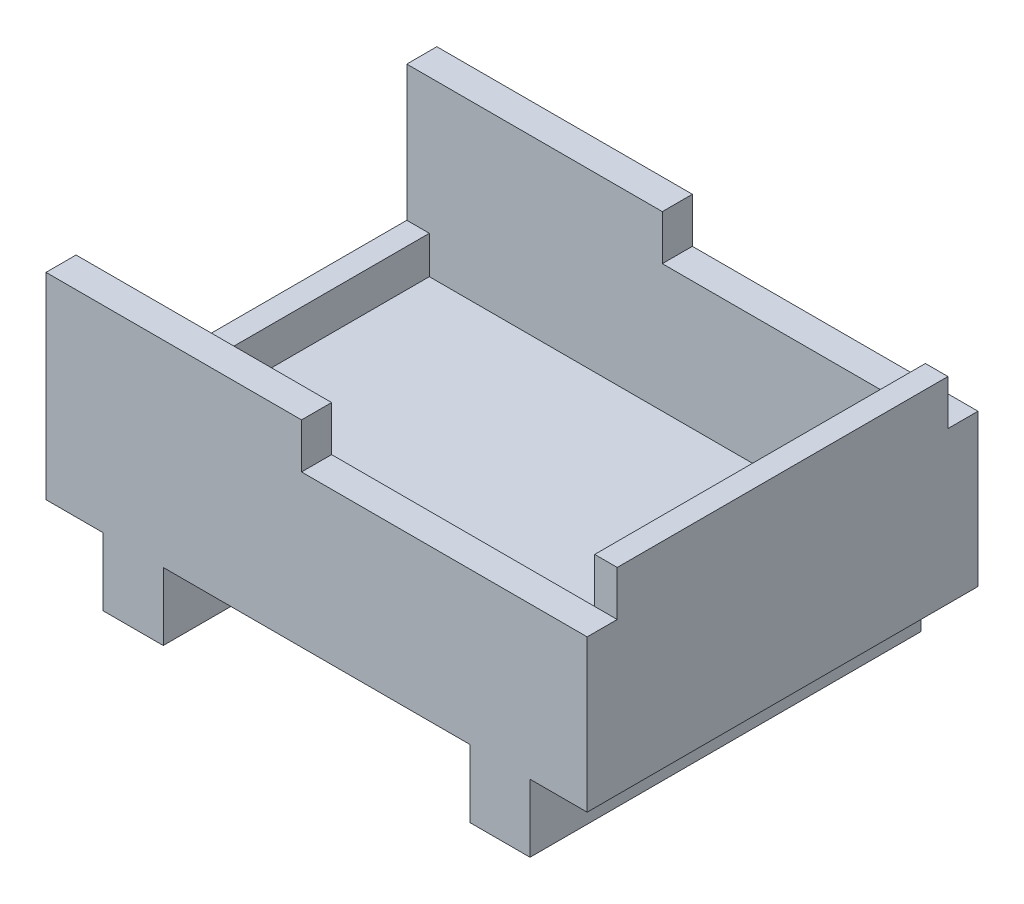
SolidWorks part; units mm, degrees
ref_plane "前视基准面" through (0, 0, 0) normal (0, 0, 1) x (1, 0, 0)
ref_plane "上视基准面" through (0, 0, 0) normal (0, 1, 0) x (1, 0, 0)
ref_plane "右视基准面" through (0, 0, 0) normal (1, 0, 0) x (0, 0, -1)
sketch "草图1" plane through (0, 0, 0) normal (0, 1, 0) x (1, 0, 0)
  line L1 (-18, 13) -> (18, 13)
  line L2 (-18, 13) -> (-18, -13)
  line L3 (-18, -13) -> (18, -13)
  line L4 (18, 13) -> (18, -13)
  line L5 (-18, 13) -> (18, -13) construction
  line L6 (-18, -13) -> (18, 13) construction
  point P0 (0, 0)
extrude "凸台-拉伸1" add sketch "草图1" along normal blind 14.6
sketch "草图2" plane through (0, 14.6, 0) normal (0, 1, 0) x (1, 0, 0)
  line L1 (-16.5, 11) -> (16.5, 11)
  line L2 (-16.5, 11) -> (-16.5, -11)
  line L3 (-16.5, -11) -> (16.5, -11)
  line L4 (16.5, 11) -> (16.5, -11)
  line L5 (-16.5, 11) -> (16.5, -11) construction
  line L6 (-16.5, -11) -> (16.5, 11) construction
  point P0 (0, 0)
extrude "切除-拉伸1" cut sketch "草图2" against normal blind 13
sketch "草图3" plane through (0, 14.6, 0) normal (0, 1, 0) x (1, 0, 0)
  line L1 (-18, 13) -> (18, 13)
  line L2 (-18, 13) -> (-18, -13)
  line L3 (-18, -13) -> (18, -13)
  line L4 (18, 13) -> (18, -13)
extrude "切除-拉伸2" cut sketch "草图3" against normal blind 4.5
sketch "草图4" plane through (0, 10.1, 0) normal (0, 1, 0) x (1, 0, 0)
  line L0 (-18, 13) -> (-18, -13) construction
  line L1 (-16.5, 11) -> (-18, 11)
  line L2 (-16.5, 11) -> (-16.5, -11)
  line L3 (-16.5, -11) -> (-18, -11)
  line L4 (-18, 11) -> (-18, -11)
extrude "切除-拉伸3" cut sketch "草图4" against normal blind 6
sketch "草图5" plane through (0, 0, 0) normal (0, -1, 0) x (-1, 0, 0)
  line L0 (0, 0) -> (0, -13) construction
  line L1 (0, -13) -> (10.2, -13) construction
  line L2 (18, -13) -> (-18, -13) construction
  line L3 (-10.2, -10) -> (-14.2, -10)
  line L4 (10.2, -13) -> (14.2, -13)
  line L5 (10.2, -13) -> (10.2, -10)
  line L6 (10.2, -10) -> (14.2, -10)
  line L7 (14.2, -13) -> (14.2, -10)
  line L8 (-14.2, -13) -> (-14.2, -10)
  line L9 (-10.2, -13) -> (-14.2, -13)
  line L10 (-10.2, -13) -> (-10.2, -10)
  line L11 (0, 0) -> (-2, 0) construction
  line L12 (-10.2, 13) -> (-10.2, 10)
  line L13 (-10.2, 13) -> (-14.2, 13)
  line L14 (-14.2, 13) -> (-14.2, 10)
  line L15 (-10.2, 10) -> (-14.2, 10)
  line L16 (10.2, 10) -> (14.2, 10)
  line L17 (14.2, 13) -> (14.2, 10)
  line L18 (10.2, 13) -> (14.2, 13)
  line L19 (10.2, 13) -> (10.2, 10)
sketch "草图7" plane through (0, 10.1, 0) normal (0, 1, 0) x (1, 0, 0)
  line L0 (16.5, 11) -> (-16.5, 11) construction
  line L1 (-18, 13) -> (-1, 13)
  line L2 (-18, 13) -> (-18, 11)
  line L3 (-18, 11) -> (-1, 11)
  line L4 (-1, 13) -> (-1, 11)
  line L5 (-18, -13) -> (18, -13) construction
  line L6 (-18, -11) -> (-1, -11)
  line L7 (-18, -11) -> (-18, -13)
  line L8 (-18, -13) -> (-1, -13)
  line L9 (-1, -11) -> (-1, -13)
  line L10 (18, -13) -> (18, 13) construction
  line L11 (16.5, -11) -> (18, -11)
  line L12 (16.5, -11) -> (16.5, 11)
  line L13 (16.5, 11) -> (18, 11)
  line L14 (18, -11) -> (18, 11)
extrude "凸台-拉伸4" add sketch "草图7" along normal blind 3
extrude "凸台-拉伸5" add sketch "草图5" along normal blind 2
sketch "草图8" plane through (0, -2, 0) normal (0, -1, 0) x (-1, 0, 0)
  line L1 (-14.2, 13) -> (-10.2, 13)
  line L2 (-14.2, 13) -> (-14.2, -13)
  line L3 (-14.2, -13) -> (-10.2, -13)
  line L4 (-10.2, 13) -> (-10.2, -13)
  line L5 (14.2, -13) -> (10.2, -13)
  line L6 (14.2, -13) -> (14.2, 13)
  line L7 (14.2, 13) -> (10.2, 13)
  line L8 (10.2, -13) -> (10.2, 13)
extrude "凸台-拉伸6" add sketch "草图8" along normal blind 2.5
